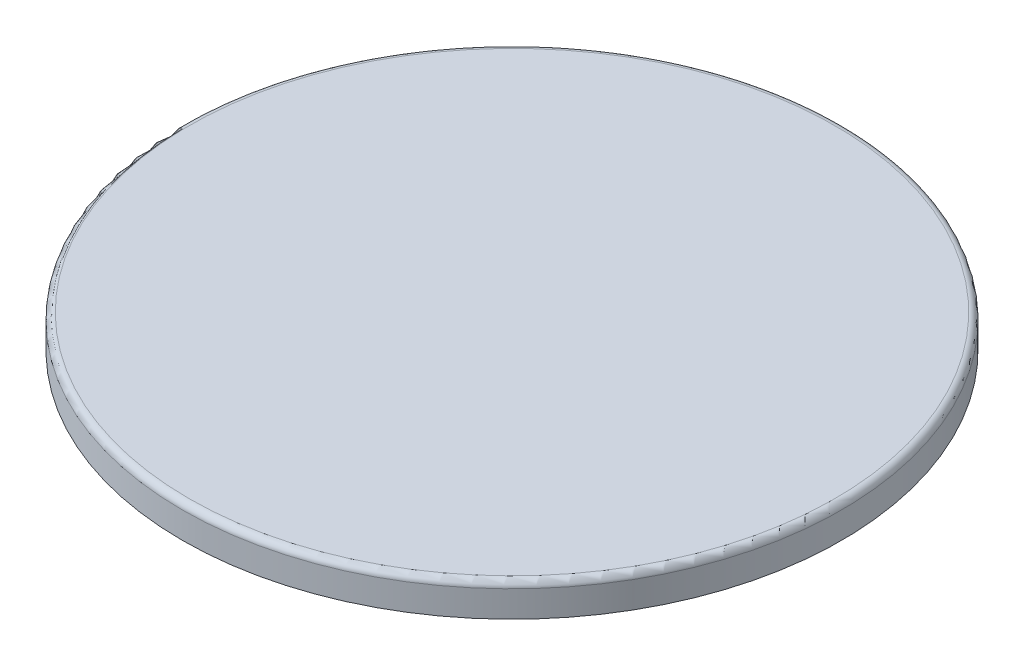
SolidWorks part; units mm, degrees
ref_plane "前视基准面" through (0, 0, 0) normal (0, 0, 1) x (1, 0, 0)
ref_plane "上视基准面" through (0, 0, 0) normal (0, 1, 0) x (1, 0, 0)
ref_plane "右视基准面" through (0, 0, 0) normal (1, 0, 0) x (0, 0, -1)
sketch "草图1" plane through (0, 0, 0) normal (0, 1, 0) x (1, 0, 0)
  circle A8 centre (0, 0) radius 5
extrude "凸台-拉伸1" add sketch "草图1" along normal blind 0.5
fillet "圆角3" radius 0.1 1 edges at (0, 0.5, 5)
